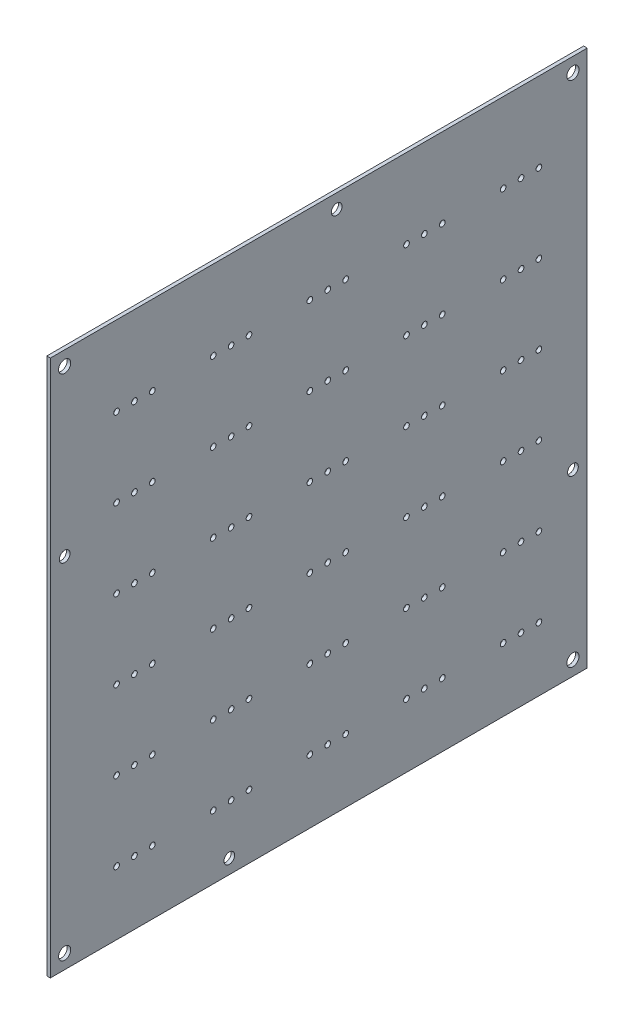
SolidWorks part; units mm, degrees
ref_plane "Front Plane" through (0, 0, 0) normal (0, 0, 1) x (1, 0, 0)
ref_plane "Top Plane" through (0, 0, 0) normal (0, 1, 0) x (1, 0, 0)
ref_plane "Right Plane" through (0, 0, 0) normal (1, 0, 0) x (0, 0, -1)
sketch "Sketch2" plane through (0, 0, 0) normal (1, 0, 0) x (0, 0, -1)
  line L1 (-40.899, 33.7667) -> (109.101, 33.7667)
  line L2 (-40.899, 33.7667) -> (-40.899, -116.2333)
  line L3 (-40.899, -116.2333) -> (109.101, -116.2333)
  line L4 (109.101, 33.7667) -> (109.101, -116.2333)
  dimension "D1" = 150
  dimension "D2" = 150
extrude "Boss-Extrude1" add sketch "Sketch2" along normal blind 1
sketch "Sketch3" plane through (1, 0, 0) normal (1, 0, 0) x (0, 0, -1)
  line L1 (-27.399, 21.2667) -> (-9.899, 21.2667)
  line L2 (-27.399, 21.2667) -> (-27.399, 3.7667)
  line L3 (-27.399, 3.7667) -> (-9.899, 3.7667)
  line L4 (-9.899, 21.2667) -> (-9.899, 3.7667)
  line L5 (-40.899, 33.7667) -> (-40.899, -116.2333) construction
  line L6 (109.101, 33.7667) -> (-40.899, 33.7667) construction
  dimension "D1" = 17.5
  dimension "D2" = 17.5
  dimension "D3" = 31
  dimension "D4" = 30
sketch "Sketch4" plane through (1, 0, 0) normal (1, 0, 0) x (0, 0, -1)
  line L1 (-27.399, 21.2667) -> (-7.399, 21.2667)
  line L2 (-27.399, 21.2667) -> (-27.399, 1.2667)
  line L3 (-27.399, 1.2667) -> (-7.399, 1.2667)
  line L4 (-7.399, 21.2667) -> (-7.399, 1.2667)
  circle A0 centre (-22.399, 11.5489) radius 0.7937
  circle A1 centre (-17.399, 11.5489) radius 0.7937
  circle A2 centre (-12.399, 11.5489) radius 0.7937
  point P7 (-27.399, 11.2667)
  point P12 (-17.8515, 12.3528)
  point P13 (0, 0)
  point P14 (0, 0)
  dimension "D3" = 1.5875
  dimension "D1" = 20
  dimension "D2" = 20
  dimension "D4" = 5
  dimension "D5" = 5
  dimension "D6" = 0
  dimension "D7" = 5
  dimension "D8" = 0
extrude "Cut-Extrude1" cut sketch "Sketch4" against normal through all contours A0 | A1 | A2
pattern_linear "LPattern1" count 5 spacing 27 along (0, 0, -1) count 6 spacing 22 along (0, -1, 0) of "Cut-Extrude1"
sketch "Sketch5" plane through (1, 0, 0) normal (1, 0, 0) x (0, 0, -1)
  line L0 (109.101, -116.2333) -> (109.101, 33.7667) construction
  line L1 (-40.899, -116.2333) -> (109.101, -116.2333) construction
  line L2 (109.101, 33.7667) -> (-40.899, 33.7667) construction
  line L3 (-40.899, 33.7667) -> (-40.899, -116.2333) construction
  point P0 (-36.899, 29.7667)
  point P1 (105.101, -112.2333)
  point P10 (105.101, 29.7667)
  point P11 (-36.899, -112.2333)
  dimension "D1" = 4
  dimension "D2" = 4
  dimension "D3" = 4
  dimension "D4" = 4
hole_wizard "M3 Clearance Hole1" positions "Sketch6" profile "Sketch7" hole size "M3" standard "ANSI Metric" end condition through all
sketch "Sketch6" plane through (1, 0, 0) normal (1, 0, 0) x (0, 0, -1)
  point P0 (-36.899, 29.7667)
  point P3 (105.101, 29.7667)
  point P6 (105.101, -112.2333)
  point P9 (-36.899, -112.2333)
sketch "Sketch7" plane through (1, 29.7667, 36.899) normal (0, 1, 0) x (0, 0, -1)
  line L0 (0, 0) -> (0, 1)
  line L1 (0, 1) -> (1.7, 1)
  line L2 (1.7, 1) -> (1.7, 0)
  line L5 (1.7, 0) -> (0, 0)
  line L11 (0, -6.35) -> (0, 107.95) construction
  dimension "Thru Hole Dia." = 3.4
  dimension "Thru Hole Depth" = 1
sketch "Sketch8" plane through (1, 0, 0) normal (1, 0, 0) x (0, 0, -1)
  line L0 (-40.899, 33.7667) -> (-40.899, -116.2333) construction
  line L5 (109.101, 33.7667) -> (-40.899, 33.7667) construction
  line L6 (-40.899, -116.2333) -> (109.101, -116.2333) construction
  line L7 (109.101, -116.2333) -> (109.101, 33.7667) construction
  circle A0 centre (39.101, 29.7667) radius 1.5
  circle A1 centre (-36.899, -16.2333) radius 1.5
  circle A2 centre (9.101, -112.2333) radius 1.5
  circle A3 centre (105.101, -66.2333) radius 1.5
  dimension "D1" = 3
  dimension "D4" = 3
  dimension "D9" = 3
  dimension "D10" = 3
  dimension "D2" = 80
  dimension "D3" = 4
  dimension "D5" = 4
  dimension "D6" = 50
  dimension "D7" = 50
  dimension "D8" = 4
  dimension "D11" = 50
  dimension "D12" = 4
extrude "Cut-Extrude2" cut sketch "Sketch8" against normal through all
